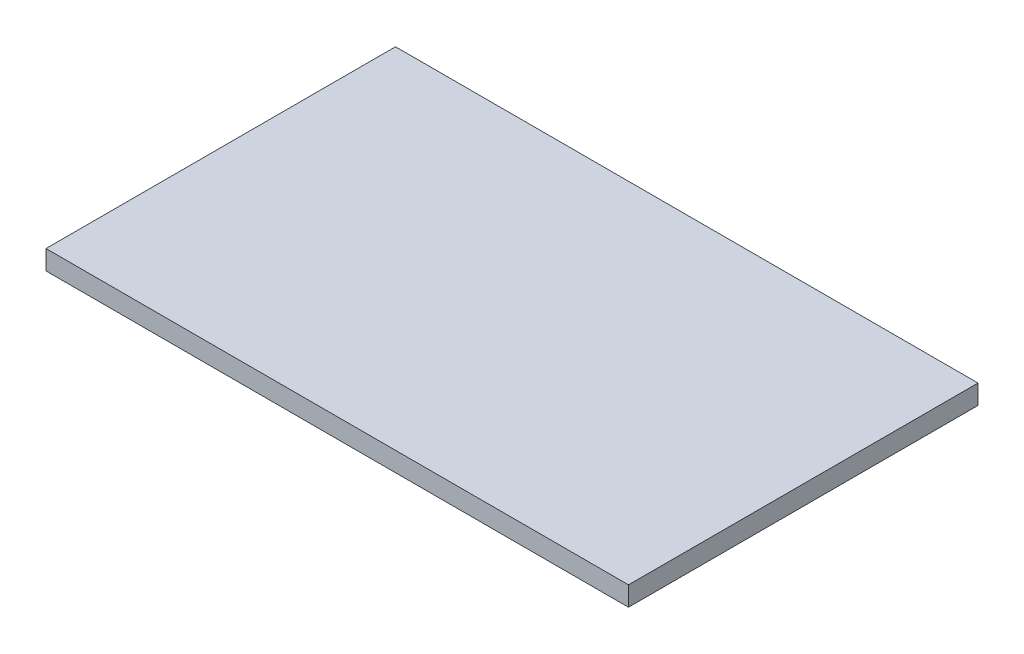
SolidWorks part; units mm, degrees
ref_plane "Front Plane" through (0, 0, 0) normal (0, 0, 1) x (1, 0, 0)
ref_plane "Top Plane" through (0, 0, 0) normal (0, 1, 0) x (1, 0, 0)
ref_plane "Right Plane" through (0, 0, 0) normal (1, 0, 0) x (0, 0, -1)
sketch "Sketch1" plane through (0, 0, 0) normal (0, 1, 0) x (1, 0, 0)
  line L1 (0, 0) -> (30, 0)
  line L2 (0, 0) -> (0, 18)
  line L3 (0, 18) -> (30, 18)
  line L4 (30, 0) -> (30, 18)
  dimension "D1" = 30
  dimension "D2" = 18
extrude "Boss-Extrude1" add sketch "Sketch1" along normal blind 1
